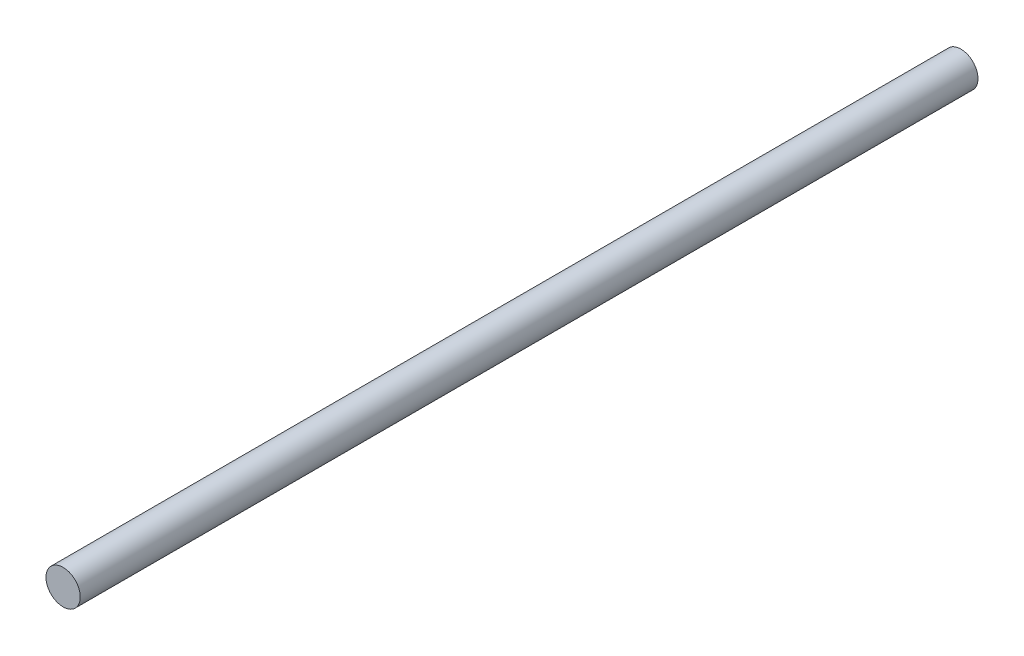
SolidWorks part; units mm, degrees
ref_plane "Alzado" through (0, 0, 0) normal (0, 0, 1) x (1, 0, 0)
ref_plane "Planta" through (0, 0, 0) normal (0, 1, 0) x (1, 0, 0)
ref_plane "Vista lateral" through (0, 0, 0) normal (1, 0, 0) x (0, 0, -1)
sketch "Croquis1" plane through (0, 0, 0) normal (0, 0, 1) x (1, 0, 0)
  circle A0 centre (0, 0) radius 0.63
  dimension "D1" = 1.26
extrude "Saliente-Extruir1" add sketch "Croquis1" along normal blind 33 contours A0
equation "\"t\"= 4"
equation "\"A_ALETA\"= ( ( ( tan ( \"ANG_ALETA\" ) ) * \"L_ALETA\" ) + \"A_BASE\" )"
equation "\"A_CAJA\"= ( 2 * \"A_BASE\" ) + \"GAP_ALETAS\""
equation "\"L_ALETA\"=90.000000"
equation "\"TAU_ALETA\"= ( \"L_ALETA\" / ( log ( ( \"A_ALETA\" ) + 1 ) ) )"
equation "\"E_ALETA\"=5.5"
equation "\"R_SONDA\"= 2.05"
equation "\"D_SONDA\"=20.000000"
equation "\"L_CAJA\"=25.000000"
equation "\"D1@Croquis1\" = ( \"R_C_SONDA\" * 2 )"
equation "\"D1@Saliente-Extruir1\" = \"L_CI\" + \"ALARGUE\""
equation "\"A_BASE\"= ( \"L_DIE\" - \"E_CAJA\" )"
equation "\"E_CAJA\"= 2.5"
equation "\"W_CAJA\"= \"A_CAJA\" * \"CONST_CAJA\""
equation "\"W_CONC\"= ( \"W_CAJA\" / \"CONST_CONC\" ) "
equation "\"A_CONC\"= ( \"A_CAJA\" / \"CONST_CONC\" )"
equation "\"L_CONC\"= \"D_SONDA\" - \"OFFSET_CONC\""
equation "\"W_ALETA\"=70.000000"
equation "\"GAP_ALETAS\"=2"
equation "\"D1@Croquis2\" = ( \"E_CI_SONDA\" )"
equation "\"D1@Saliente-Extruir2\" = \"GAP_ALETAS\" / 2"
equation "\"D1@Croquis3\" = ( \"R_SONDA\" - \"E_CE_SONDA\" ) * 2"
equation "\"D2@Croquis3\" = \"E_CI_SONDA\""
equation "\"L_DIE_SONDA\"= ( \"GAP_ALETAS\" / 4 )"
equation "\"D1@Croquis4\" = ( \"E_CI_SONDA\" * 2 )"
equation "\"D2@Croquis4\" = ( \"R_SONDA\" - \"E_CE_SONDA\" ) * 2"
equation "\"D1@Saliente-Extruir4\" = \"A_BASE\" + \"E_CAJA\" + \"L_DIE_SONDA\""
equation "\"D1@Croquis5\" = ( \"R_SONDA\" - \"E_CE_SONDA\" ) * 2"
equation "\"D2@Croquis5\" = 2 * \"R_SONDA\""
equation "\"D1@Saliente-Extruir5\" = \"E_CAJA\" + \"A_BASE\""
equation "\"CONST_CONC\"=2.000000"
equation "\"K\"= 1.5"
equation "\"L_DIE\"= 15"
equation "\"L_CI\"= 18"
equation "\"CONST_CAJA\"=2.000000"
equation "\"ANG_ALETA\"=15.000000"
equation "\"R_C_SONDA\"= 0.63"
equation "\"TOLERANCIA\"= 0.5"
equation "\"OFFSET_CONC\"= ( 2 * \"R_TORNILLO\" )"
equation "\"R_TORNILLO\"=2.600000"
equation "\"ALARGUE\"=15"
